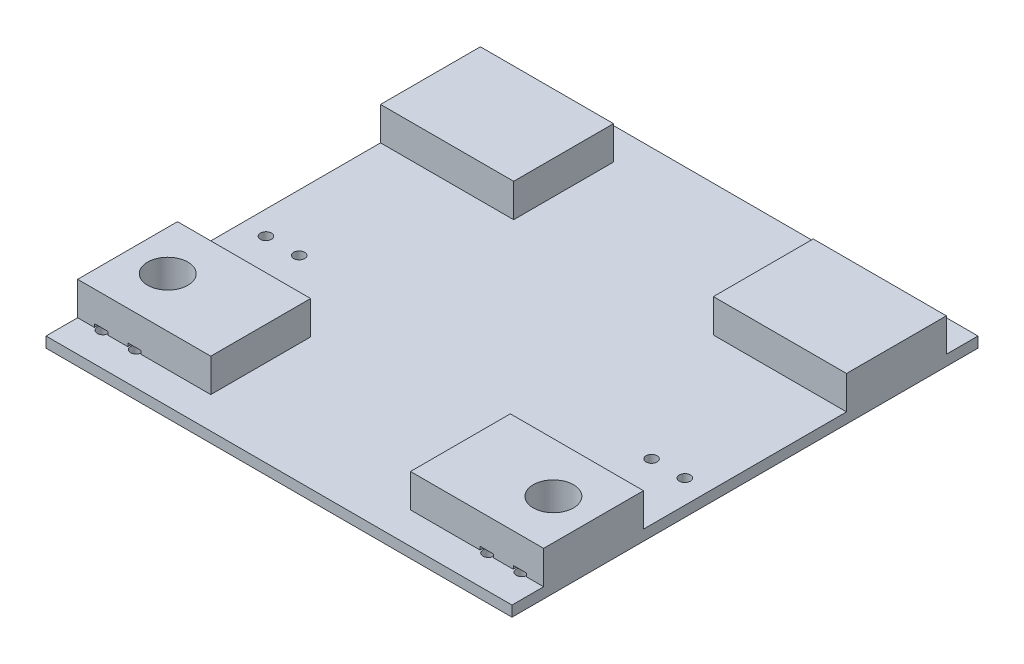
SolidWorks part; units mm, degrees
ref_plane "Front Plane" through (0, 0, 0) normal (0, 0, 1) x (1, 0, 0)
ref_plane "Top Plane" through (0, 0, 0) normal (0, 1, 0) x (1, 0, 0)
ref_plane "Right Plane" through (0, 0, 0) normal (1, 0, 0) x (0, 0, -1)
sketch "Sketch1" plane through (0, 0, 0) normal (0, 1, 0) x (1, 0, 0)
  line L1 (-70, -70) -> (70, -70)
  line L2 (-70, -70) -> (-70, 70)
  line L3 (-70, 70) -> (70, 70)
  line L4 (70, -70) -> (70, 70)
  line L5 (-70, -70) -> (70, 70) construction
  line L6 (-70, 70) -> (70, -70) construction
  point P0 (0, 0)
  dimension "D1" = 140
  dimension "D2" = 140
extrude "Boss-Extrude1" add sketch "Sketch1" along normal blind 3.175
sketch "Sketch2" plane through (0, 3.175, 0) normal (0, 1, 0) x (1, 0, 0)
  line L0 (0, -1.7463) -> (0, 1.7463) construction
  line L1 (-45, -30.5) -> (45, -30.5) construction
  line L2 (-45, -30.5) -> (-45, 30.5) construction
  line L3 (-45, 30.5) -> (45, 30.5) construction
  line L4 (45, -30.5) -> (45, 30.5) construction
  line L5 (-45, -30.5) -> (45, 30.5) construction
  line L6 (-45, 30.5) -> (45, -30.5) construction
  line L11 (60, -30.5) -> (30, -30.5)
  line L12 (-60, -60.5) -> (-30, -60.5)
  line L21 (-60, -60.5) -> (-60, -30.5)
  line L22 (-60, -30.5) -> (-30, -30.5)
  line L23 (30, -60.5) -> (30, -30.5)
  line L24 (-30, -60.5) -> (-30, -30.5)
  line L25 (-60, -60.5) -> (-30, -30.5) construction
  line L26 (-60, -30.5) -> (-30, -60.5) construction
  line L27 (60, -60.5) -> (30, -60.5)
  line L28 (60, -60.5) -> (60, -30.5)
  line L29 (-1.7463, 0) -> (1.7463, 0) construction
  line L34 (-60, 30.5) -> (-30, 30.5)
  line L35 (-30, 60.5) -> (-30, 30.5)
  line L36 (-60, 60.5) -> (-30, 60.5)
  line L37 (-60, 60.5) -> (-60, 30.5)
  line L38 (-60, -30.5) -> (-70, -30.5) construction
  line L39 (-70, 70) -> (-70, -70) construction
  circle A0 centre (0, 0) radius 40 construction
  point P0 (0, 0)
  point P8 (-45, -45.5)
  dimension "D3" = 80
  dimension "D1" = 90
  dimension "D2" = 61
  dimension "D4" = 30
  dimension "D5" = 30
extrude "Boss-Extrude2" add sketch "Sketch2" along normal blind 10
sketch "Sketch11" plane through (-60, 0, 0) normal (-1, 0, 0) x (0, 0, 1)
  line L1 (30.5, 3.175) -> (60.5, 3.175)
  line L2 (30.5, 3.175) -> (30.5, 13.175)
  line L3 (30.5, 13.175) -> (60.5, 13.175)
  line L4 (60.5, 3.175) -> (60.5, 13.175)
  line L5 (30.5, 3.175) -> (60.5, 13.175) construction
  line L6 (30.5, 13.175) -> (60.5, 3.175) construction
  point P4 (45.5, 8.175)
extrude "Boss-Extrude3" add sketch "Sketch11" along normal up to surface (10 mm away) up to face at (-70, 1.5875, 0)
sketch "Sketch13" plane through (60, 0, 0) normal (1, 0, 0) x (0, 0, -1)
  line L1 (-60.5, 3.175) -> (-30.5, 3.175)
  line L2 (-60.5, 3.175) -> (-60.5, 13.175)
  line L3 (-60.5, 13.175) -> (-30.5, 13.175)
  line L4 (-30.5, 3.175) -> (-30.5, 13.175)
  line L5 (-60.5, 3.175) -> (-30.5, 13.175) construction
  line L6 (-60.5, 13.175) -> (-30.5, 3.175) construction
  point P4 (-45.5, 8.175)
extrude "Boss-Extrude4" add sketch "Sketch13" along normal up to surface (10 mm away) up to face at (70, 1.5875, 0)
mirror "Mirror1" about plane through (0, 0, 0) normal (1, 0, 0) of "Boss-Extrude2"
sketch "Sketch16" plane through (60, 0, 0) normal (1, 0, 0) x (0, 0, -1)
  line L1 (30.5, 3.175) -> (60.5, 3.175)
  line L2 (30.5, 3.175) -> (30.5, 13.175)
  line L3 (30.5, 13.175) -> (60.5, 13.175)
  line L4 (60.5, 3.175) -> (60.5, 13.175)
  line L5 (30.5, 3.175) -> (60.5, 13.175) construction
  line L6 (30.5, 13.175) -> (60.5, 3.175) construction
  point P4 (45.5, 8.175)
extrude "Boss-Extrude6" add sketch "Sketch16" along normal up to surface (10 mm away) up to face at (70, 4.8813, 22.75)
sketch "Sketch17" plane through (-60, 0, 0) normal (-1, 0, 0) x (0, 0, 1)
  line L1 (-60.5, 3.175) -> (-30.5, 3.175)
  line L2 (-60.5, 3.175) -> (-60.5, 13.175)
  line L3 (-60.5, 13.175) -> (-30.5, 13.175)
  line L4 (-30.5, 3.175) -> (-30.5, 13.175)
  line L5 (-60.5, 3.175) -> (-30.5, 13.175) construction
  line L6 (-60.5, 13.175) -> (-30.5, 3.175) construction
  point P4 (-45.5, 8.175)
extrude "Boss-Extrude7" add sketch "Sketch17" along normal up to surface (10 mm away) up to face at (-70, 4.8813, 22.75)
sketch "Sketch18" plane through (0, 13.175, 0) normal (0, 1, 0) x (1, 0, 0)
  line L0 (-30, -30.5) -> (-70, -30.5) construction
  line L1 (-30, -60.5) -> (-60, -60.5) construction
  line L2 (-30, -60.5) -> (-30, -30.5) construction
  line L3 (-30, -30.5) -> (-60, -30.5) construction
  line L4 (-60, -60.5) -> (-60, -30.5) construction
  line L5 (-30, -60.5) -> (-60, -30.5) construction
  line L6 (-30, -30.5) -> (-60, -60.5) construction
  line L8 (-45, -30.5) -> (-45, 30.5) construction
  line L9 (-70, 30.5) -> (-30, 30.5) construction
  line L10 (-51.4643, 30.5) -> (-51.4643, -60.5) construction
  line L11 (-70, 30.5) -> (-30, 30.5) construction
  line L12 (-45, -45.5) -> (-60, -45.5) construction
  line L13 (0, -1.7463) -> (0, 1.7463) construction
  circle A0 centre (-45, 0) radius 6.4643 construction
  circle A1 centre (-57.9286, -45.5) radius 6.4643 construction
  circle A2 centre (-57.9286, -45.5) radius 6.05
  circle A3 centre (57.9286, -45.5) radius 6.05
  point P4 (-45, -45.5)
  dimension "D2" = 12.9286
  dimension "D3" = 12.9286
  dimension "D4" = 12.1
  dimension "D1" = 30
extrude "Cut-Extrude1" cut sketch "Sketch18" against normal up to surface (13.175 mm away) up to face at (0, 0, 0)
sketch "Sketch20" plane through (0, 0, 0) normal (0, -1, 0) x (-1, 0, 0)
  line L0 (-45, 30.5) -> (-30, 30.5) construction
  line L1 (45, 30.5) -> (-45, 30.5) construction
  line L2 (45, 30.5) -> (45, -30.5) construction
  line L3 (45, -30.5) -> (-45, -30.5) construction
  line L4 (-45, 30.5) -> (-45, -30.5) construction
  line L5 (45, 30.5) -> (-45, -30.5) construction
  line L6 (45, -30.5) -> (-45, 30.5) construction
  line L7 (-30, 30.5) -> (-30, 60.5) construction
  line L8 (-70, -70) -> (-70, 70) construction
  line L9 (-30, 60.5) -> (-70, 60.5) construction
  line L10 (-30, 60.5) -> (-30, 30.5) construction
  line L11 (-30, 30.5) -> (-70, 30.5) construction
  line L12 (-70, 60.5) -> (-70, 30.5) construction
  line L13 (-30, 60.5) -> (-70, 30.5) construction
  line L14 (-30, 30.5) -> (-70, 60.5) construction
  line L15 (-30, 45.5) -> (-70, 45.5) construction
  line L16 (-50, 30.5) -> (-50, 60.5) construction
  line L18 (0, 1.7463) -> (0, -1.7463) construction
  line L19 (-1.7463, 0) -> (1.7463, 0) construction
  circle A0 centre (-35, 56.75) radius 0.8
  circle A1 centre (-65, 56.75) radius 0.8
  circle A2 centre (-65, 34.25) radius 0.8
  circle A3 centre (-35, 34.25) radius 0.8
  circle A4 centre (35, 56.75) radius 0.8
  circle A5 centre (65, 56.75) radius 0.8
  circle A6 centre (65, 34.25) radius 0.8
  circle A7 centre (35, 34.25) radius 0.8
  circle A8 centre (65, -34.25) radius 0.8
  circle A9 centre (35, -34.25) radius 0.8
  circle A10 centre (35, -56.75) radius 0.8
  circle A11 centre (65, -56.75) radius 0.8
  circle A12 centre (-35, -34.25) radius 0.8
  circle A13 centre (-65, -34.25) radius 0.8
  circle A14 centre (-65, -56.75) radius 0.8
  circle A15 centre (-35, -56.75) radius 0.8
  point P0 (0, 0)
  point P10 (-50, 45.5)
  dimension "D5" = 1.6
  dimension "D1" = 90
  dimension "D2" = 61
  dimension "D3" = 15
  dimension "D4" = 30
  dimension "D6" = 5
sketch "Sketch21" plane through (0, 0, 0) normal (0, -1, 0) x (-1, 0, 0)
  line L0 (57.9286, -45.5) -> (57.9286, -55.5) construction
  line L1 (57.9286, -65) -> (57.9286, -55.5) construction
  line L2 (67.9286, -55.5) -> (47.9286, -55.5)
  line L3 (67.9286, -55.5) -> (67.9286, -15.5)
  line L4 (67.9286, -15.5) -> (47.9286, -15.5)
  line L5 (47.9286, -55.5) -> (47.9286, -15.5)
  line L6 (67.9286, -55.5) -> (47.9286, -15.5)
  line L7 (67.9286, -15.5) -> (47.9286, -55.5)
  line L8 (67.9286, -6) -> (47.9286, -6) construction
  line L9 (67.9286, -6) -> (67.9286, -65) construction
  line L10 (67.9286, -65) -> (47.9286, -65) construction
  line L11 (47.9286, -6) -> (47.9286, -65) construction
  line L12 (67.9286, -6) -> (47.9286, -65) construction
  line L13 (67.9286, -65) -> (47.9286, -6) construction
  line L14 (67.9286, -11) -> (47.9286, -11) construction
  line L15 (67.9286, -11) -> (67.9286, -60) construction
  line L16 (67.9286, -60) -> (47.9286, -60) construction
  line L17 (47.9286, -11) -> (47.9286, -60) construction
  line L18 (67.9286, -11) -> (47.9286, -60) construction
  line L19 (67.9286, -60) -> (47.9286, -11) construction
  line L20 (62.9286, -60) -> (52.9286, -60) construction
  line L21 (67.9286, -35.5) -> (47.9286, -35.5) construction
  line L22 (0, 1.7463) -> (0, -1.7463) construction
  line L23 (-67.9286, -15.5) -> (-47.9286, -15.5)
  line L24 (-47.9286, -55.5) -> (-47.9286, -15.5)
  line L25 (-67.9286, -55.5) -> (-47.9286, -55.5)
  line L26 (-67.9286, -55.5) -> (-67.9286, -15.5)
  circle A0 centre (57.9286, -45.5) radius 2.45 construction
  circle A1 centre (62.9286, -60) radius 1.65
  circle A2 centre (52.9286, -60) radius 1.65
  circle A3 centre (52.9286, -11) radius 1.65
  circle A4 centre (62.9286, -11) radius 1.65
  circle A5 centre (-52.9286, -11) radius 1.65
  circle A6 centre (-62.9286, -11) radius 1.65
  circle A7 centre (-52.9286, -60) radius 1.65
  circle A8 centre (-62.9286, -60) radius 1.65
  point P8 (57.9286, -35.5)
  point P9 (57.9286, -55.5)
  point P10 (57.9286, -35.5)
  point P15 (57.9286, -35.5)
  point P23 (57.9286, -60)
  dimension "D1" = 4.9
  dimension "D7" = 3.3
  dimension "D2" = 10
  dimension "D3" = 40
  dimension "20" = 20
  dimension "D4" = 49
  dimension "D5" = 59
  dimension "D6" = 10
extrude "Cut-Extrude2" cut sketch "Sketch21" against normal up to surface (3.175 mm away) contours A6 | A5 | A8 | A7 | A3 | A4 | A2 | A1 up to face at (0, 3.175, 0)
sketch "Sketch22" plane through (0, 3.175, 0) normal (0, -1, 0) x (-1, 0, 0)
  line L0 (0, 1.7463) -> (0, -1.7463) construction
  circle A0 centre (62.9286, -60) radius 2.05
  circle A1 centre (52.9286, -60) radius 2.05
  circle A2 centre (-52.9286, -60) radius 2.05
  circle A3 centre (-62.9286, -60) radius 2.05
  dimension "D1" = 4.1
  dimension "D2" = 4.1
extrude "Cut-Extrude3" cut sketch "Sketch22" against normal blind 1
